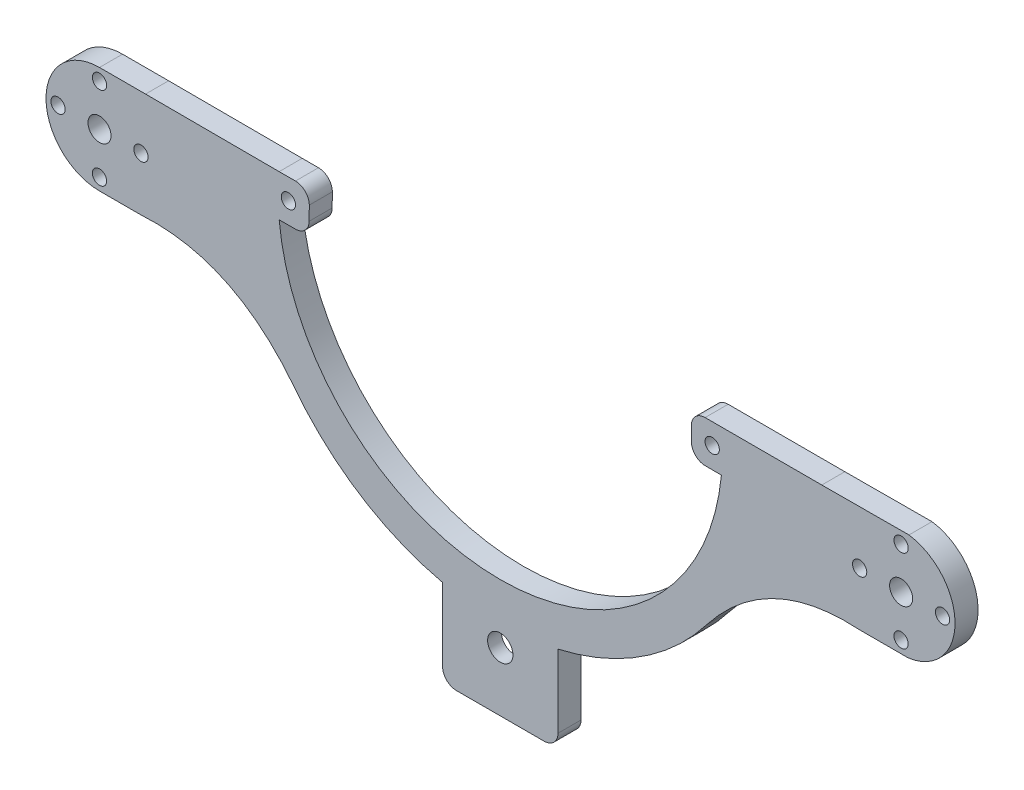
SolidWorks part; units mm, degrees
ref_plane "Front Plane" through (0, 0, 0) normal (0, 0, 1) x (1, 0, 0)
ref_plane "Top Plane" through (0, 0, 0) normal (0, 1, 0) x (1, 0, 0)
ref_plane "Right Plane" through (0, 0, 0) normal (1, 0, 0) x (0, 0, -1)
sketch "Sketch2" plane through (0, 0, 0) normal (0, 0, 1) x (1, 0, 0)
  line L0 (-9.5251, -73.8356) -> (0, -73.8356)
  line L1 (-48.0066, 4.4865) -> (-44.4658, 4.4888)
  line L2 (0, 0) -> (0, 24.8373) construction
  line L5 (-47.9983, -4.5715) -> (-44.4813, -4.5601)
  line L6 (-11.5, -51.5) -> (-11.5, -70.5)
  line L7 (-9.5, -49.5) -> (9.5, -49.5)
  line L9 (-9.5, -72.5) -> (9.5, -72.5)
  line L10 (11.5, -51.5) -> (11.5, -70.5)
  line L11 (-11.5, -49.5) -> (-11.5, -72.5)
  line L12 (11.5, -49.5) -> (11.5, -72.5)
  line L15 (88.7161, 4.5429) -> (69.7953, 4.4721)
  line L16 (12.5251, -55.0099) -> (12.5251, -70.8356)
  line L23 (88.5279, -18.6559) -> (78.0066, -18.6559)
  line L24 (41.464, 1.4621) -> (41.4911, -1.5868)
  line L25 (47.9983, -4.5715) -> (44.4813, -4.5601)
  line L26 (-12.5251, -55.0099) -> (-12.5251, -70.8356)
  line L27 (0, -73.8356) -> (9.5251, -73.8356)
  line L28 (-41.464, 1.4621) -> (-41.4911, -1.5868)
  line L29 (48.0066, 4.4865) -> (44.4658, 4.4888)
  line L30 (-77.0066, 4.5691) -> (-94.5842, -15.8429) construction
  line L32 (-97.0066, 4.5691) -> (-97.0066, 4.2784) construction
  line L34 (-77.0066, 4.5691) -> (-77.0066, -1.14) construction
  line L35 (11.5, -49.5) -> (-11.5, -72.5) construction
  line L36 (0, 0) -> (0, -61) construction
  line L37 (87.0066, -7.0434) -> (91.9752, 0.1387) construction
  line L38 (87.0066, -7.0434) -> (87.0066, 1.9566) construction
  line L39 (87.0066, -7.0434) -> (96.0066, -7.0434) construction
  line L40 (-87.0066, -18.6559) -> (-78.0066, -18.6559)
  line L41 (-77.0066, -5.8591) -> (-77.0066, -17.8979) construction
  line L42 (69.7953, 4.4721) -> (45.4021, 4.4882)
  line L43 (0, 73.8356) -> (9.5251, 73.8356)
  line L44 (-48.0066, 4.4865) -> (-77.0066, 4.5691)
  line L45 (-87.0066, 4.5691) -> (-77.0066, 4.5691) construction
  line L46 (-97.0066, -1.14) -> (-97.0066, -12.9468) construction
  line L47 (-97.0066, -18.3791) -> (-97.0066, -18.6559) construction
  line L48 (-96.8335, -18.4549) -> (-97.0066, -18.6559) construction
  line L49 (-10, 71) -> (10, 71)
  line L52 (-9.5251, 73.8356) -> (0, 73.8356)
  line L53 (-77.0066, 4.5691) -> (-87.0066, 4.5691)
  arc A12 (-44.4658, 4.4888) -> (-41.464, 1.4621) centre (-44.4639, 1.4888) cw
  arc A13 (-12.5251, -70.8356) -> (-9.5251, -73.8356) centre (-9.5251, -70.8356) ccw
  arc A14 (12.5251, -70.8356) -> (9.5251, -73.8356) centre (9.5251, -70.8356) cw
  arc A15 (44.8639, -34.2082) -> (12.5251, -55.0099) centre (0, 0) cw
  circle A19 centre (46, 0) radius 1.55
  arc A20 (41.4911, -1.5868) -> (44.4813, -4.5601) centre (44.491, -1.5601) ccw
  arc A23 (-41.4911, -1.5868) -> (-44.4813, -4.5601) centre (-44.491, -1.5601) cw
  arc A24 (-96.8335, -18.4549) -> (-98.7183, -15.6698) centre (-95.7183, -15.6698) cw
  arc A25 (44.4658, 4.4888) -> (41.464, 1.4621) centre (44.4639, 1.4888) ccw
  arc A26 (-47.9983, -4.5715) -> (47.9983, -4.5715) centre (0, 0) ccw
  circle A27 centre (-46, 0) radius 1.55
  arc A28 (-44.8639, -34.2082) -> (-12.5251, -55.0099) centre (0, 0) ccw
  circle A29 centre (-87.0066, -7.0434) radius 2.5
  circle A30 centre (87.0066, -7.0434) radius 2.5
  arc A32 (-97.0066, 4.2784) -> (-98.7183, 1.5691) centre (-95.7183, 1.5691) ccw
  circle A34 centre (87.0066, 1.9566) radius 1.55
  circle A35 centre (96.0066, -7.0434) radius 1.55
  circle A36 centre (87.0066, -16.0434) radius 1.55
  circle A37 centre (78.0066, -7.0434) radius 1.55
  circle A38 centre (-78.0066, -7.0434) radius 1.55
  circle A39 centre (-87.0066, -16.0434) radius 1.55
  circle A40 centre (-96.0066, -7.0434) radius 1.55
  circle A41 centre (-87.0066, 1.9566) radius 1.55
  circle A42 centre (-87.0066, -7.0434) radius 2.5
  circle A43 centre (0, -61) radius 2.75
  arc A46 (85.4853, -18.6559) -> (85.2104, 4.5298) centre (87.0066, -7.0434) ccw
  arc A47 (-87.0066, 4.5691) -> (-87.0066, -18.6559) centre (-87.0066, -7.0434) ccw
  arc A48 (12.5251, 70.8356) -> (9.5251, 73.8356) centre (9.5251, 70.8356) ccw
  arc A49 (-12.5251, 70.8356) -> (-9.5251, 73.8356) centre (-9.5251, 70.8356) cw
  arc A50 (11.5, -70.5) -> (9.5, -72.5) centre (9.5, -70.5) cw
  arc A51 (-9.5, -72.5) -> (-11.5, -70.5) centre (-9.5, -70.5) cw
  arc A52 (-11.5, -51.5) -> (-9.5, -49.5) centre (-9.5, -51.5) cw
  arc A53 (9.5, -49.5) -> (11.5, -51.5) centre (9.5, -51.5) cw
  spline S0 degree 2 poles (-78.0066, -18.6559) (-58.0434, -17.373) (-44.8639, -34.2082) knots 0 0 0 1 1 1
  spline S1 degree 2 poles (78.0066, -18.6559) (58.0434, -17.373) (44.8639, -34.2082) knots 0 0 0 1 1 1
  point P4 (0, -73.8356)
  point P19 (-98.0306, -17.8979)
  point P30 (-12.5251, -73.8356)
  point P34 (12.5251, -73.8356)
  point P40 (-41.4465, 2.7628)
  point P42 (-41.4465, -2.7628)
  point P58 (41.4465, -2.7628)
  point P59 (41.4465, 2.7628)
  point P71 (90.9776, 0.8173)
  point P74 (-86.0186, -17.8979)
  point P77 (-90.9776, 0.8173)
  point P79 (98.0306, -17.8979)
  point P120 (12.5251, 73.8356)
  point P121 (-12.5251, 73.8356)
  dimension "D1" = 20
  dimension "D2" = 3
  dimension "D3" = 3
  dimension "D4" = 23
  dimension "D6" = 3
  dimension "D7" = 3
  dimension "D8" = 3
  dimension "D11" = 5.5
  dimension "D12" = 2
  dimension "D5" = 23
  dimension "D9" = 96.0132
  dimension "D10" = 20
extrude "Boss-Extrude1" add sketch "Sketch2" along normal blind 5
sketch "Sketch3" plane through (0, 0, 0) normal (0, 0, -1) x (-1, 0, 0)
  line L16 (-98.7183, 1.5691) -> (-98.7183, -15.6698)
  line L17 (-96.0066, -18.6559) -> (-78.0066, -18.6559)
  line L18 (-12.5251, -55.4245) -> (-12.5251, -70.8356)
  line L19 (-9.5251, -73.8356) -> (0, -73.8356)
  line L20 (0, -73.8356) -> (9.5251, -73.8356)
  line L21 (12.5251, -70.8356) -> (12.5251, -55.4245)
  line L22 (78.0066, -18.6559) -> (96.0066, -18.6559)
  line L23 (98.7183, -15.6698) -> (98.7183, 1.5691)
  line L24 (95.7183, 4.5691) -> (48.0066, 4.5691)
  line L25 (48.0066, 4.5691) -> (44, 3.9311)
  line L26 (41.4718, 0.939) -> (41.4966, -1.5904)
  line L27 (43.5848, -4.4191) -> (47.6808, -5.7256)
  line L28 (-47.6808, -5.7256) -> (-43.5848, -4.4191)
  line L29 (-41.4966, -1.5904) -> (-41.4718, 0.939)
  line L30 (-44, 3.9311) -> (-48.0066, 4.5691)
  line L31 (-48.0066, 4.5691) -> (-95.7183, 4.5691)
  line L35 (-9.5251, -73.8356) -> (0, -73.8356)
  line L36 (0, -73.8356) -> (9.5251, -73.8356)
  line L48 (0, 0) -> (20.9207, 0)
  line L59 (0, -73.8356) -> (-9.5251, -73.8356) construction
  line L60 (9.5, -49.5) -> (-9.5, -49.5)
  line L61 (-11.5, -51.5) -> (-11.5, -70.5)
  line L62 (-9.5, -72.5) -> (9.5, -72.5)
  line L63 (11.5, -70.5) -> (11.5, -51.5)
  line L64 (9.5, -49.5) -> (-9.5, -49.5)
  line L65 (-11.5, -51.5) -> (-11.5, -70.5)
  line L66 (-9.5, -72.5) -> (9.5, -72.5)
  line L67 (11.5, -70.5) -> (11.5, -51.5)
  line L68 (9.5251, -73.8356) -> (0, -73.8356) construction
  line L69 (12.5251, -55.0099) -> (12.5251, -70.8356) construction
  line L86 (0, -73.8356) -> (-9.5251, -73.8356)
  line L87 (9.5251, -73.8356) -> (0, -73.8356)
  line L88 (12.5251, -55.0099) -> (12.5251, -70.8356)
  arc A19 (-95.7183, 4.5691) -> (-98.7183, 1.5691) centre (-95.7183, 1.5691) ccw
  arc A20 (-98.7183, -15.6698) -> (-96.0066, -18.6559) centre (-95.7183, -15.6698) ccw
  arc A21 (-45.1854, -34.4534) -> (-12.5251, -55.4245) centre (0, 0) ccw
  arc A22 (-12.5251, -70.8356) -> (-9.5251, -73.8356) centre (-9.5251, -70.8356) ccw
  arc A23 (9.5251, -73.8356) -> (12.5251, -70.8356) centre (9.5251, -70.8356) ccw
  arc A24 (12.5251, -55.4245) -> (45.1854, -34.4534) centre (0, 0) ccw
  arc A25 (96.0066, -18.6559) -> (98.7183, -15.6698) centre (95.7183, -15.6698) ccw
  arc A26 (98.7183, 1.5691) -> (95.7183, 4.5691) centre (95.7183, 1.5691) ccw
  arc A27 (44, 3.9311) -> (41.4718, 0.939) centre (44.4717, 0.9684) ccw
  arc A28 (41.4966, -1.5904) -> (43.5848, -4.4191) centre (44.4965, -1.5609) ccw
  arc A29 (-47.6808, -5.7256) -> (47.6808, -5.7256) centre (0, 0) ccw
  arc A30 (-43.5848, -4.4191) -> (-41.4966, -1.5904) centre (-44.4965, -1.5609) ccw
  arc A31 (-41.4718, 0.939) -> (-44, 3.9311) centre (-44.4717, 0.9684) ccw
  arc A35 (-12.5251, -70.8356) -> (-9.5251, -73.8356) centre (-9.5251, -70.8356) ccw
  arc A36 (9.5251, -73.8356) -> (12.5251, -70.8356) centre (9.5251, -70.8356) ccw
  arc A37 (12.5251, -55.4245) -> (45.1854, -34.4534) centre (0, 0) ccw
  arc A42 (-47.6808, -5.7256) -> (47.6808, -5.7256) centre (0, 0) ccw
  circle A84 centre (0, -61) radius 2.75
  circle A85 centre (0, -61) radius 2.75
  arc A87 (-12.5251, -70.8356) -> (-9.5251, -73.8356) centre (-9.5251, -70.8356) ccw construction
  arc A88 (9.5251, -73.8356) -> (12.5251, -70.8356) centre (9.5251, -70.8356) ccw construction
  arc A89 (-9.5, -49.5) -> (-11.5, -51.5) centre (-9.5, -51.5) ccw
  arc A90 (-11.5, -70.5) -> (-9.5, -72.5) centre (-9.5, -70.5) ccw
  arc A91 (9.5, -72.5) -> (11.5, -70.5) centre (9.5, -70.5) ccw
  arc A92 (11.5, -51.5) -> (9.5, -49.5) centre (9.5, -51.5) ccw
  arc A93 (-9.5, -49.5) -> (-11.5, -51.5) centre (-9.5, -51.5) ccw
  arc A94 (-11.5, -70.5) -> (-9.5, -72.5) centre (-9.5, -70.5) ccw
  arc A95 (9.5, -72.5) -> (11.5, -70.5) centre (9.5, -70.5) ccw
  arc A96 (11.5, -51.5) -> (9.5, -49.5) centre (9.5, -51.5) ccw
  arc A97 (12.5251, -55.0099) -> (44.8639, -34.2082) centre (0, 0) ccw construction
  arc A101 (-47.9983, -4.5715) -> (47.9983, -4.5715) centre (0, 0) ccw construction
  arc A110 (-12.5251, -70.8356) -> (-9.5251, -73.8356) centre (-9.5251, -70.8356) ccw
  arc A111 (9.5251, -73.8356) -> (12.5251, -70.8356) centre (9.5251, -70.8356) ccw
  arc A112 (12.5251, -55.0099) -> (44.8639, -34.2082) centre (0, 0) ccw
  arc A116 (-47.9983, -4.5715) -> (47.9983, -4.5715) centre (0, 0) ccw
  parabola Q2 (-78.0066, -18.6559) -> (-45.1854, -34.4534) focus (-68.2775, -36.3212) apex (-62.3384, -20.8315)
  parabola Q3 (45.1854, -34.4534) -> (78.0066, -18.6559) focus (68.2775, -36.3212) apex (62.3384, -20.8315)
  point P98 (46, 0)
  point P119 (47.4823, 0.4532)
  point P121 (-46, 0)
  point P122 (-44.5177, 0.4532)
  point P124 (-87.0066, 1.9566)
  point P125 (-85.5243, 2.4098)
  point P127 (-87.0066, -7.0434)
  point P128 (-84.6158, -6.3125)
  point P130 (87.0066, -7.0434)
  point P131 (89.3974, -6.3125)
  point P133 (87.0066, -7.0434)
  point P134 (89.3974, -6.3125)
  point P136 (87.0066, 1.9566)
  point P137 (88.4889, 2.4098)
  point P139 (96.0066, -7.0434)
  point P140 (97.4889, -6.5902)
  point P142 (87.0066, -16.0434)
  point P143 (88.4889, -15.5902)
  point P145 (78.0066, -7.0434)
  point P146 (79.4889, -6.5902)
  point P148 (-78.0066, -7.0434)
  point P149 (-76.5243, -6.5902)
  point P151 (-87.0066, -16.0434)
  point P152 (-85.5243, -15.5902)
  point P154 (-96.0066, -7.0434)
  point P155 (-94.5243, -6.5902)
  dimension "D4" = 0
  dimension "D29" = 0
  dimension "D30" = 0
extrude "Cut-Extrude1" cut sketch "Sketch3" against normal blind 2
